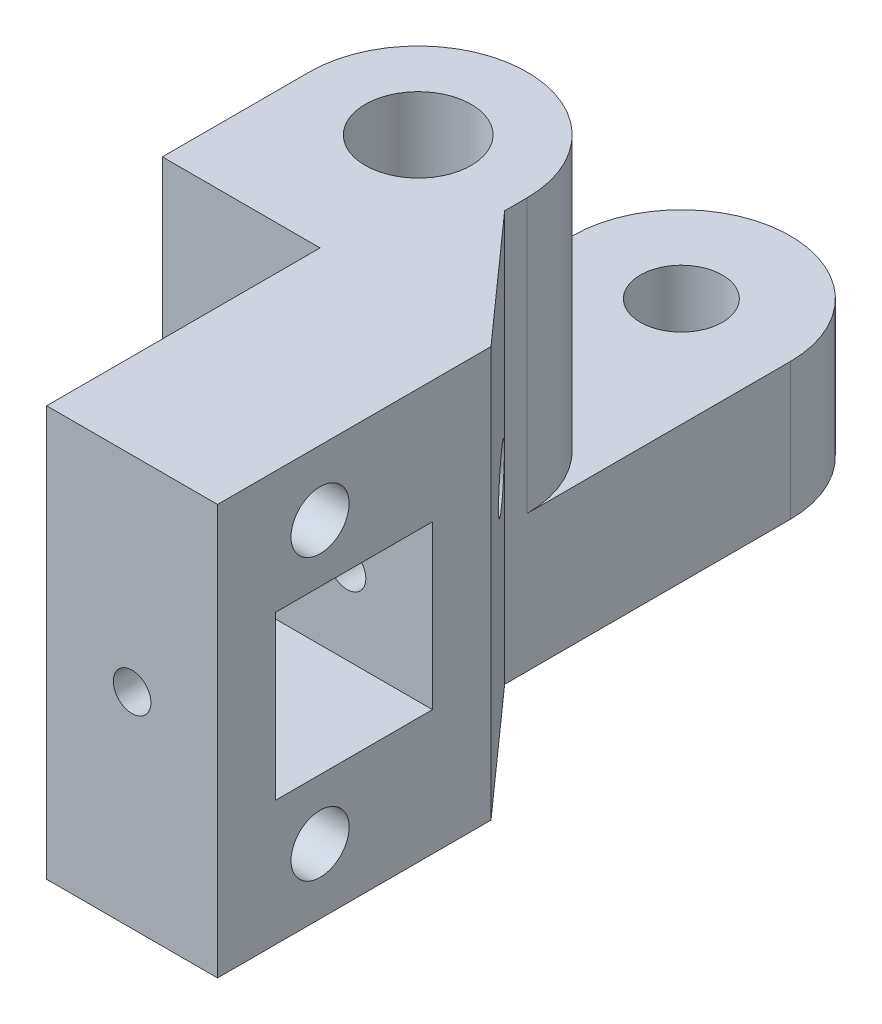
SolidWorks part; units mm, degrees
ref_plane "前视基准面" through (0, 0, 0) normal (0, 0, 1) x (1, 0, 0)
ref_plane "上视基准面" through (0, 0, 0) normal (0, 1, 0) x (1, 0, 0)
ref_plane "右视基准面" through (0, 0, 0) normal (1, 0, 0) x (0, 0, -1)
sketch "草图1" plane through (0, 0, 0) normal (0, 1, 0) x (1, 0, 0)
  line L11 (74.5174, 16.1852) -> (74.5174, -83.8148)
  line L12 (74.5174, -83.8148) -> (106.3833, -83.8148)
  line L13 (106.3833, -83.8148) -> (106.3833, 16.1852)
  line L15 (90.4503, -22.1888) -> (90.4503, -83.8148) construction
  circle A3 centre (90.4503, 16.1852) radius 6
  circle A4 centre (90.4503, -22.3148) radius 7.75
  arc A5 (74.5174, 16.1852) -> (106.3833, 16.1852) centre (90.4503, 16.1852) cw
  dimension "D7" = 12
  dimension "D8" = 15.5
  dimension "D6" = 100
  dimension "D9" = 38.5
extrude "凸台-拉伸1" add sketch "草图1" along normal blind 60
sketch "草图3" plane through (0, 60, 0) normal (0, 1, 0) x (1, 0, 0)
  circle A0 centre (90.4503, 16.1852) radius 15.9329
extrude "切除-拉伸1" cut sketch "草图3" against normal blind 40
sketch "草图4" plane through (0, 60, 0) normal (0, 1, 0) x (1, 0, 0)
  line L0 (74.5174, 16.1852) -> (74.5174, -22.3148)
  line L1 (106.3833, 16.1852) -> (106.3833, -22.3148)
  line L2 (74.5174, 16.1852) -> (106.3833, 16.1852)
  arc A0 (106.3833, -22.3148) -> (74.5174, -22.3148) centre (90.4503, -22.3148) ccw
extrude "切除-拉伸2" cut sketch "草图4" against normal blind 40
sketch "草图5" plane through (74.5174, 0, 0) normal (-1, 0, 0) x (0, 0, 1)
  line L0 (68.8148, 0) -> (68.8148, 60) construction
  line L1 (-16.1852, 0) -> (83.8148, 0) construction
  line L2 (22.3148, 60) -> (83.8148, 60) construction
  circle A0 centre (68.8148, 9.5) radius 4.25
  circle A1 centre (68.8148, 50.5) radius 4.25
  point P10 (68.8148, 30)
  dimension "D4" = 8.5
  dimension "D5" = 8.5
  dimension "D1" = 15
  dimension "D2" = 20.5
  dimension "D3" = 20.5
extrude "切除-拉伸3" cut sketch "草图5" against normal through all
sketch "草图6" plane through (106.3833, 0, 0) normal (1, 0, 0) x (0, 0, -1)
  line L0 (-83.8148, 60) -> (-53.8148, 60)
  line L1 (-83.8148, 60) -> (-22.3148, 60) construction
  line L2 (-53.8148, 60) -> (-53.8148, 0)
  line L3 (-83.8148, 0) -> (16.1852, 0) construction
  line L4 (-53.8148, 0) -> (-83.8148, 0)
  line L5 (-83.8148, 0) -> (-83.8148, 60)
  circle A0 centre (-68.8148, 50.5) radius 4.25 construction
  circle A1 centre (-68.8148, 50.5) radius 4.25
  circle A2 centre (-68.8148, 9.5) radius 4.25 construction
  circle A3 centre (-68.8148, 9.5) radius 4.25
  dimension "D1" = 30
extrude "凸台-拉伸2" add sketch "草图6" along normal blind 30
mirror "镜向1" about plane through (136.3833, 0, 0) normal (-1, 0, 0) of bodies 105
delete or keep bodies "实体-删除/保留 1" type keep bodies bodies 107
sketch "草图8" plane through (136.3833, 0, 0) normal (-1, 0, 0) x (0, 0, 1)
  line L0 (53.8148, 0) -> (53.8148, 60)
  line L1 (53.8148, 60) -> (83.8148, 60)
  line L2 (83.8148, 60) -> (83.8148, 0)
  line L3 (83.8148, 0) -> (53.8148, 0)
extrude "切除-拉伸4" cut sketch "草图8" against normal blind 30
sketch "草图10" plane through (0, 60, 0) normal (0, 1, 0) x (1, 0, 0)
  line L0 (198.2491, -83.8148) -> (198.2491, -43.8148)
  line L1 (198.2491, -22.3148) -> (198.2491, -83.8148) construction
  line L2 (198.2491, -43.8148) -> (166.3833, -43.8148)
  line L3 (166.3833, -83.8148) -> (166.3833, -22.3148) construction
  line L4 (166.3833, -43.8148) -> (166.3833, -83.8148)
  line L5 (166.3833, -83.8148) -> (198.2491, -83.8148)
  dimension "D1" = 40
extrude "切除-拉伸6" cut sketch "草图10" against normal blind 110
sketch "草图13" plane through (0, 0, 43.8148) normal (0, 0, 1) x (1, 0, 0)
  line L0 (198.2491, 60) -> (166.3833, 60) construction
  line L1 (189.4592, 60) -> (214.4592, 60)
  line L2 (189.4592, 60) -> (189.4592, 0)
  line L3 (189.4592, 0) -> (214.4592, 0)
  line L4 (214.4592, 60) -> (214.4592, 0)
  line L5 (189.4592, 60) -> (214.4592, 0) construction
  line L6 (189.4592, 0) -> (214.4592, 60) construction
  point P4 (201.9592, 30)
  dimension "D1" = 25
extrude "凸台-拉伸4" add sketch "草图13" along normal blind 40
sketch "草图14" plane through (0, 60, 0) normal (0, 1, 0) x (1, 0, 0)
  line L1 (214.4592, -43.8148) -> (198.2491, -43.8148)
  line L2 (198.2491, -43.8148) -> (198.2491, -25.6048)
  line L3 (198.2491, -22.3148) -> (198.2491, -43.8148) construction
  line L4 (198.2491, -25.6048) -> (214.4592, -43.8148)
  dimension "D1" = 16.21
  dimension "D2" = 18.21
extrude "凸台-拉伸5" add sketch "草图14" against normal blind 60
sketch "草图15" plane through (189.4592, 0, 0) normal (-1, 0, 0) x (0, 0, 1)
  line L5 (52.3712, 42.0911) -> (75.3712, 42.0911)
  line L6 (52.3712, 42.0911) -> (52.3712, 18.2787)
  line L7 (52.3712, 18.2787) -> (75.3712, 18.2787)
  line L8 (75.3712, 42.0911) -> (75.3712, 18.2787)
  line L9 (63.8712, 18.2787) -> (63.8712, 42.0911) construction
  line L10 (52.3712, 30.1849) -> (75.3712, 30.1849) construction
  circle A0 centre (68.8148, 9.5) radius 4.25
  circle A1 centre (68.8148, 50.5) radius 4.25
  point P0 (63.8712, 30.1849)
  point P4 (63.9912, 41.1013)
  point P9 (73.278, 30.1849)
  dimension "D1" = 23
extrude "切除-拉伸7" cut sketch "草图15" against normal through all
sketch "草图16" plane through (0, 0, 83.8148) normal (0, 0, 1) x (1, 0, 0)
  line L0 (201.9592, 60) -> (201.9592, 0) construction
  line L1 (214.4592, 60) -> (189.4592, 60) construction
  line L2 (189.4592, 0) -> (214.4592, 0) construction
  circle A0 centre (201.9592, 30) radius 2.75
  dimension "D1" = 5.5
extrude "切除-拉伸8" cut sketch "草图16" against normal through all
ref_plane "基准面1" through (0, 0, 34.3712) normal (0, 0, 1) x (1, 0, 0)
sketch "草图17" plane through (0, 0, 34.3712) normal (0, 0, 1) x (1, 0, 0)
  circle A0 centre (201.9592, 30) radius 3.5
  dimension "D1" = 7
extrude "切除-拉伸9" cut sketch "草图17" against normal blind 60
